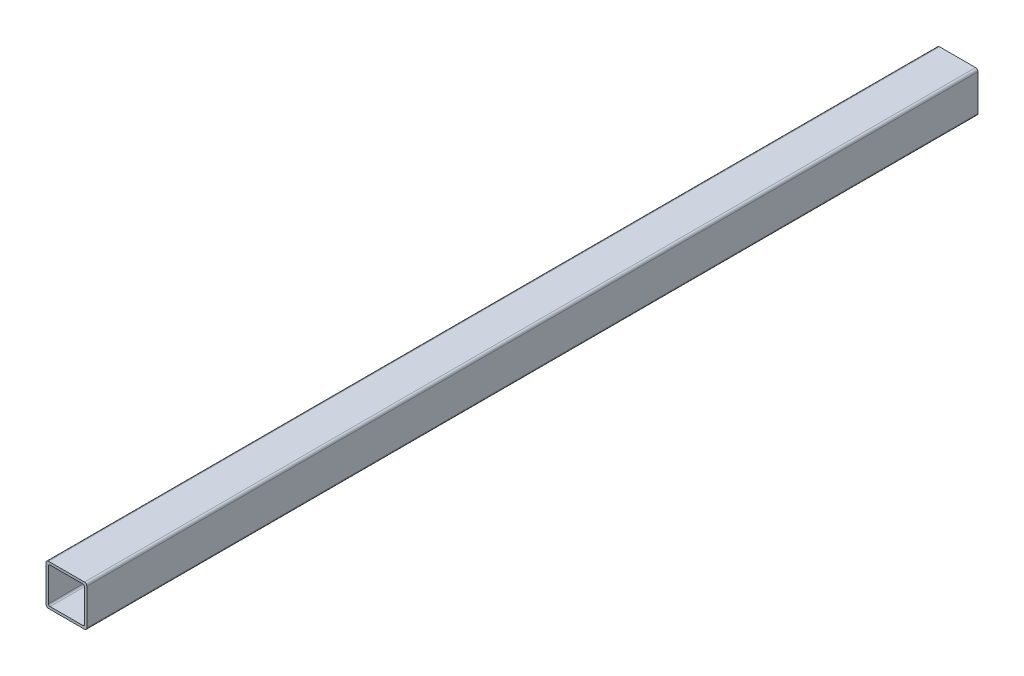
SolidWorks part; units mm, degrees
material "AISI 1020"
ref_plane "Спереди" through (0, 0, 0) normal (0, 0, 1) x (1, 0, 0)
ref_plane "Сверху" through (0, 0, 0) normal (0, 1, 0) x (1, 0, 0)
ref_plane "Справа" through (0, 0, 0) normal (1, 0, 0) x (0, 0, -1)
sketch "Эскиз1" plane through (0, 0, 0) normal (0, 0, 1) x (1, 0, 0)
  point P0 (0, 0)
  line B0 (-22, 25) -> (22, 25)
  line B1 (-25, 22) -> (-25, -22)
  line B2 (-22, -25) -> (22, -25)
  line B3 (25, 22) -> (25, -22)
  line B4 (-20, 22) -> (20, 22)
  line B5 (-22, 20) -> (-22, -20)
  line B6 (-20, -22) -> (20, -22)
  line B7 (22, 20) -> (22, -20)
  arc B8 (-25, -22) -> (-22, -25) centre (-22, -22) ccw
  arc B9 (22, -25) -> (25, -22) centre (22, -22) ccw
  arc B10 (22, 25) -> (25, 22) centre (22, 22) cw
  arc B11 (-22, 25) -> (-25, 22) centre (-22, 22) ccw
  arc B12 (-22, -20) -> (-20, -22) centre (-20, -20) ccw
  arc B13 (20, -22) -> (22, -20) centre (20, -20) ccw
  arc B14 (20, 22) -> (22, 20) centre (20, 20) cw
  arc B15 (-20, 22) -> (-22, 20) centre (-20, 20) ccw
sketch_block_instance "Труба профильная 50х50х3-1"
sketch_block "Труба профильная 50х50х3" parameters "D3"=3, "D4"=2, "D1"=50, "D2"=3
extrude "Бобышка-Вытянуть1" add sketch "Эскиз1" against normal up to surface (1090 mm away)
